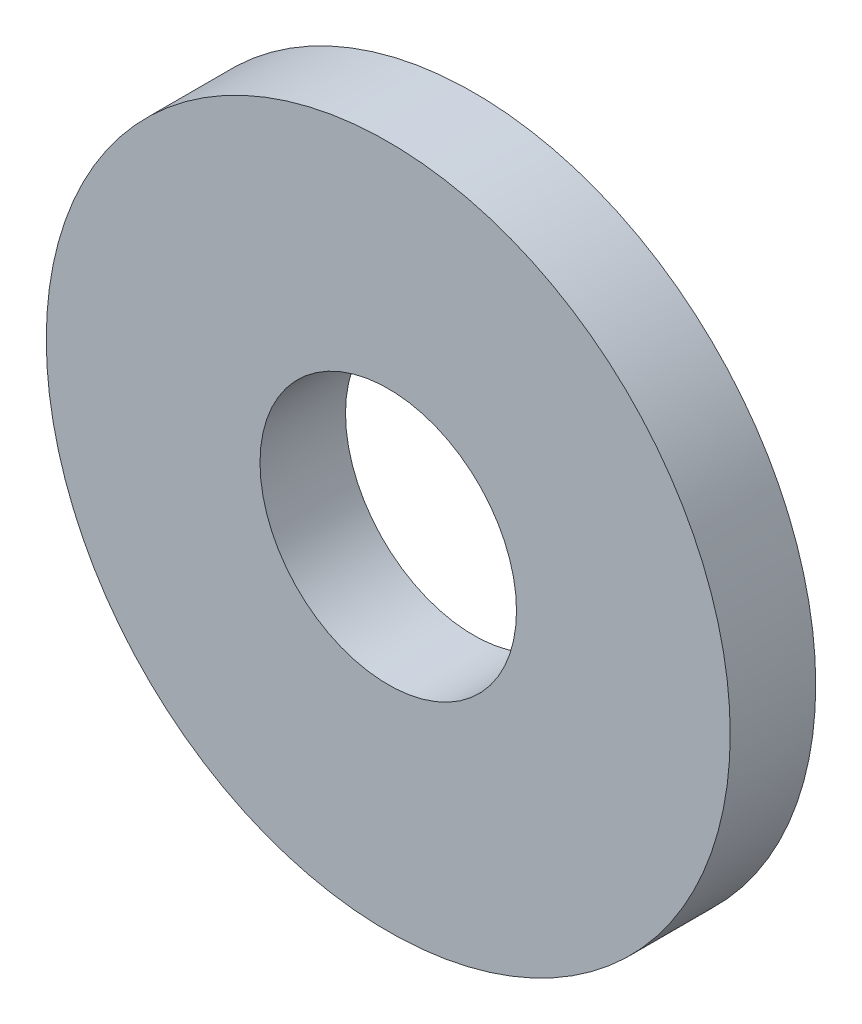
SolidWorks part; units mm, degrees
material "Alumina"
ref_plane "Front Plane" through (0, 0, 0) normal (0, 0, 1) x (1, 0, 0)
ref_plane "Top Plane" through (0, 0, 0) normal (0, 1, 0) x (1, 0, 0)
ref_plane "Right Plane" through (0, 0, 0) normal (1, 0, 0) x (0, 0, -1)
sketch "Sketch1" plane through (0, 0, 0) normal (0, 0, 1) x (1, 0, 0)
  circle A0 centre (0, 0) radius 20
  circle A1 centre (0, 0) radius 7.5
  dimension "D1" = 40
  dimension "D2" = 15
extrude "Boss-Extrude1" add sketch "Sketch1" along normal blind 5
